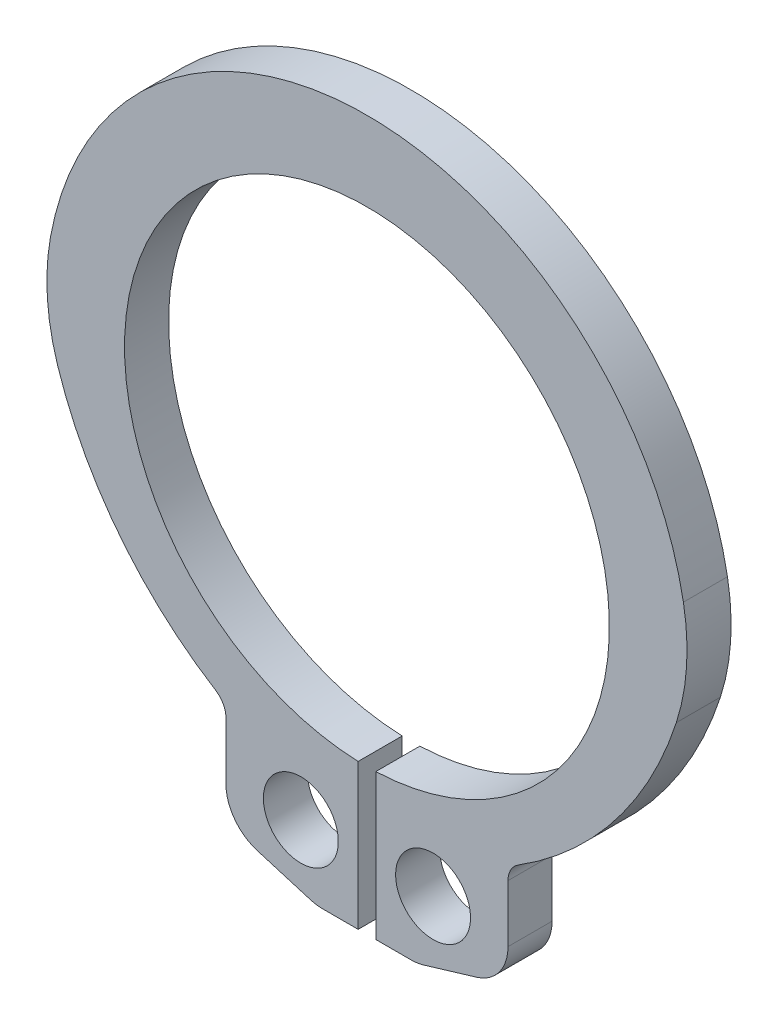
SolidWorks part; units mm, degrees
material "Stainless Steel (ferritic)"
ref_plane "Front Plane" through (0, 0, 0) normal (0, 0, 1) x (1, 0, 0)
ref_plane "Top Plane" through (0, 0, 0) normal (0, 1, 0) x (1, 0, 0)
ref_plane "Right Plane" through (0, 0, 0) normal (1, 0, 0) x (0, 0, -1)
ref_plane "Plane1" through (0, 0, -0.5) normal (0, 0, -1) x (-1, 0, 0)
sketch "Sketch1" plane through (0, 0, -0.5) normal (0, 0, -1) x (-1, 0, 0)
  line L0 (-3.2, -6.1382) -> (-3.2, -7.4359)
  line L1 (-2.4875, -8.3937) -> (-1.2863, -8.7542)
  line L2 (-0.9988, -8.7964) -> (-0.2, -8.7964)
  line L3 (-0.2, -8.7964) -> (-0.2, -5.4964)
  line L4 (0.2, -5.4964) -> (0.2, -8.7964)
  line L5 (0.2, -8.7964) -> (0.9988, -8.7964)
  line L6 (1.2863, -8.7542) -> (2.4875, -8.3937)
  line L7 (3.2, -7.4359) -> (3.2, -6.1382)
  circle A0 centre (-1.5, -7.2964) radius 0.85
  circle A1 centre (1.5, -7.2964) radius 0.85
  arc A2 (-7.0182, -1.1259) -> (-3.4351, -5.7142) centre (1.0694, 1.4967) ccw
  arc A3 (-3.4351, -5.7142) -> (-3.2, -6.1382) centre (-3.7, -6.1382) cw
  arc A4 (-3.2, -7.4359) -> (-2.4875, -8.3937) centre (-2.2, -7.4359) ccw
  arc A5 (-1.2863, -8.7542) -> (-0.9988, -8.7964) centre (-0.9988, -7.7964) ccw
  arc A6 (-0.2, -5.4964) -> (0.2, -5.4964) centre (0, 0) cw
  arc A7 (0.9988, -8.7964) -> (1.2863, -8.7542) centre (0.9988, -7.7964) ccw
  arc A8 (2.4875, -8.3937) -> (3.2, -7.4359) centre (2.2, -7.4359) ccw
  arc A9 (3.2, -6.1382) -> (3.4351, -5.7142) centre (3.7, -6.1382) cw
  arc A10 (3.4351, -5.7142) -> (7.0182, -1.1259) centre (-1.0694, 1.4967) ccw
  arc A11 (7.0182, -1.1259) -> (7.1794, 1.3216) centre (2.262, 0.4164) ccw
  arc A12 (7.1794, 1.3216) -> (-7.1794, 1.3216) centre (0, 0) ccw
  arc A13 (-7.1794, 1.3216) -> (-7.0182, -1.1259) centre (-2.262, 0.4164) ccw
extrude "Boss-Extrude1" add sketch "Sketch1" against normal blind 1
